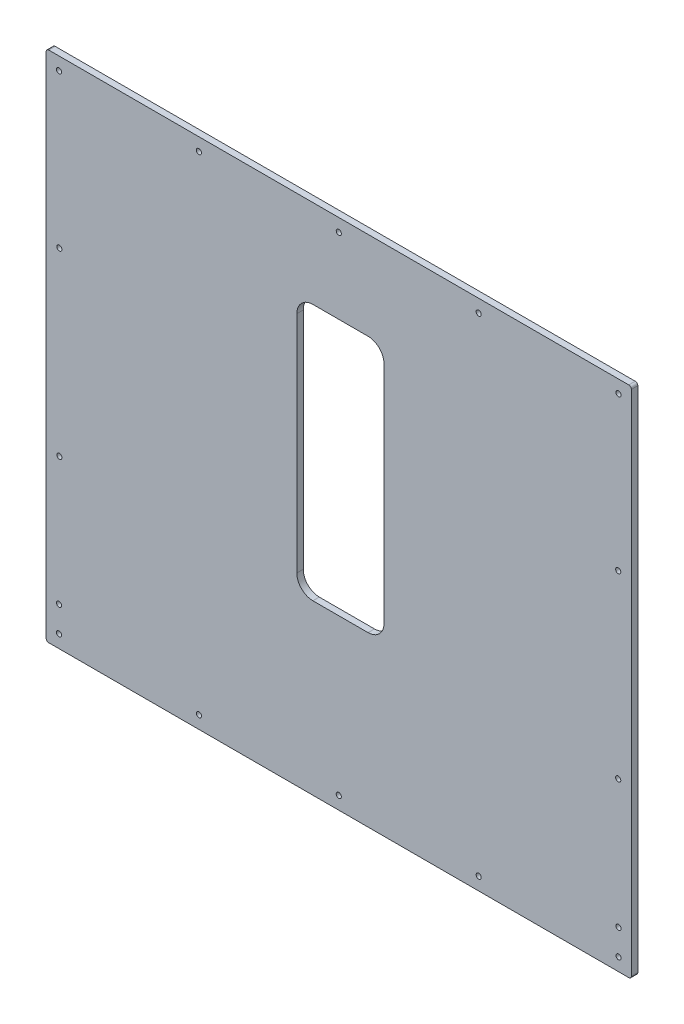
SolidWorks part; units mm, degrees
ref_plane "Plan de face" through (0, 0, 0) normal (0, 0, 1) x (1, 0, 0)
ref_plane "Plan de dessus" through (0, 0, 0) normal (0, 1, 0) x (1, 0, 0)
ref_plane "Plan de droite" through (0, 0, 0) normal (1, 0, 0) x (0, 0, -1)
sketch "Esquisse1" plane through (0, 0, 0) normal (0, 0, 1) x (1, 0, 0)
  line L1 (-452, -400) -> (452, -400)
  line L2 (-456, -396) -> (-456, 396)
  line L3 (-452, 400) -> (452, 400)
  line L4 (456, -396) -> (456, 396)
  line L5 (-456, -400) -> (456, 400) construction
  line L6 (-456, 400) -> (456, -400) construction
  line L7 (0, 400) -> (0, -400) construction
  line L8 (-456, 0) -> (456, 0) construction
  arc A0 (-456, 396) -> (-452, 400) centre (-452, 396) cw
  arc A1 (456, 396) -> (452, 400) centre (452, 396) ccw
  arc A2 (452, -400) -> (456, -396) centre (452, -396) ccw
  arc A3 (-456, -396) -> (-452, -400) centre (-452, -396) ccw
  circle A4 centre (436, 380) radius 4
  circle A5 centre (435.5, -140) radius 4
  circle A6 centre (435.5, 141) radius 4
  circle A7 centre (-435.5, -140) radius 4
  circle A8 centre (-436, 380) radius 4
  circle A9 centre (-435.5, 141) radius 4
  circle A10 centre (436, -380) radius 4
  circle A11 centre (436, -340) radius 4
  circle A12 centre (-436, -340) radius 4
  circle A13 centre (-436, -380) radius 4
  circle A14 centre (218, -380) radius 4
  circle A15 centre (0, -380) radius 4
  circle A16 centre (-218, -380) radius 4
  circle A17 centre (-218, 380) radius 4
  circle A18 centre (0, 380) radius 4
  circle A19 centre (218, 380) radius 4
  point P0 (0, 0)
  dimension "D3" = 4
  dimension "D4" = 4
  dimension "D5" = 4
  dimension "D6" = 4
  dimension "D7" = 8
  dimension "D8" = 20
  dimension "D9" = 20
  dimension "D11" = 20.5
  dimension "D12" = 259
  dimension "D13" = 8
  dimension "D14" = 2
  dimension "D1" = 912
  dimension "D2" = 800
  dimension "D15" = 4
  dimension "D10" = 2
extrude "Boss.-Extru.1" add sketch "Esquisse1" along normal blind 10
sketch "Esquisse2" plane through (0, 0, 10) normal (0, 0, 1) x (1, 0, 0)
  line L0 (-40.3797, -137.5014) -> (45.5772, -137.5014)
  line L1 (-65.3797, -112.5014) -> (-65.3797, 237.4986)
  line L2 (70.5772, -112.5014) -> (70.5772, 237.4986)
  line L3 (-40.3797, 262.4986) -> (45.5772, 262.4986)
  arc A0 (-40.3797, 262.4986) -> (-65.3797, 237.4986) centre (-40.3797, 237.4986) ccw
  arc A1 (45.5772, 262.4986) -> (70.5772, 237.4986) centre (45.5772, 237.4986) cw
  arc A2 (70.5772, -112.5014) -> (45.5772, -137.5014) centre (45.5772, -112.5014) cw
  arc A3 (-65.3797, -112.5014) -> (-40.3797, -137.5014) centre (-40.3797, -112.5014) ccw
  point P9 (70.5772, 262.4986)
  point P12 (70.5772, -137.5014)
  dimension "D2" = 25
  dimension "D1" = 400
extrude "Enlèv. mat.-Extru.1" cut sketch "Esquisse2" against normal through all
